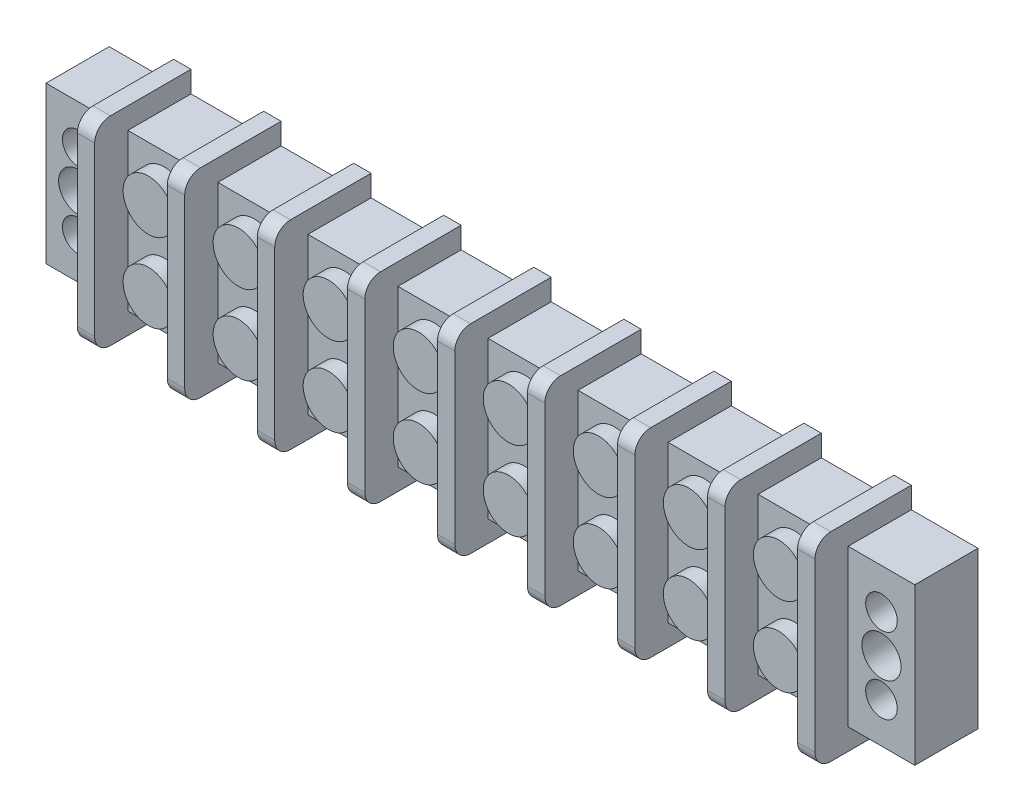
SolidWorks part; units mm, degrees
ref_plane "Front Plane" through (0, 0, 0) normal (0, 0, 1) x (1, 0, 0)
ref_plane "Top Plane" through (0, 0, 0) normal (0, 1, 0) x (1, 0, 0)
ref_plane "Right Plane" through (0, 0, 0) normal (1, 0, 0) x (0, 0, -1)
sketch "Sketch1" plane through (0, 0, 0) normal (0, 0, 1) x (1, 0, 0)
  line L1 (0, 25.146) -> (139.7, 25.146)
  line L2 (0, 25.146) -> (0, 0)
  line L3 (0, 0) -> (139.7, 0)
  line L4 (139.7, 25.146) -> (139.7, 0)
  dimension "D1" = 139.7
  dimension "D2" = 25.146
extrude "Boss-Extrude1" add sketch "Sketch1" along normal blind 10.16
sketch "Sketch3" plane through (0, 0, 0) normal (0, 0, 1) x (1, 0, 0)
  line L0 (0, 12.573) -> (139.7, 12.573) construction
  line L1 (97.2312, 28.575) -> (100.0252, 28.575)
  line L2 (97.2312, 28.575) -> (97.2312, -3.429)
  line L3 (97.2312, -3.429) -> (100.0252, -3.429)
  line L4 (126.1872, 28.575) -> (128.9812, 28.575)
  line L5 (126.1872, 28.575) -> (126.1872, -3.429)
  line L6 (126.1872, -3.429) -> (128.9812, -3.429)
  line L7 (128.9812, 28.575) -> (128.9812, -3.429)
  line L8 (111.7092, 28.575) -> (114.5032, 28.575)
  line L9 (111.7092, 28.575) -> (111.7092, -3.429)
  line L10 (111.7092, -3.429) -> (114.5032, -3.429)
  line L11 (114.5032, 28.575) -> (114.5032, -3.429)
  line L12 (100.0252, 28.575) -> (100.0252, -3.429)
  line L13 (82.7532, 28.575) -> (85.5472, 28.575)
  line L14 (82.7532, 28.575) -> (82.7532, -3.429)
  line L15 (82.7532, -3.429) -> (85.5472, -3.429)
  line L16 (85.5472, 28.575) -> (85.5472, -3.429)
  line L17 (68.2752, 28.575) -> (71.0692, 28.575)
  line L18 (68.2752, 28.575) -> (68.2752, -3.429)
  line L19 (68.2752, -3.429) -> (71.0692, -3.429)
  line L20 (71.0692, 28.575) -> (71.0692, -3.429)
  line L21 (53.7972, 28.575) -> (56.5912, 28.575)
  line L22 (53.7972, 28.575) -> (53.7972, -3.429)
  line L23 (53.7972, -3.429) -> (56.5912, -3.429)
  line L24 (56.5912, 28.575) -> (56.5912, -3.429)
  line L25 (39.3192, 28.575) -> (42.1132, 28.575)
  line L26 (39.3192, 28.575) -> (39.3192, -3.429)
  line L27 (39.3192, -3.429) -> (42.1132, -3.429)
  line L28 (42.1132, 28.575) -> (42.1132, -3.429)
  line L29 (24.8412, 28.575) -> (27.6352, 28.575)
  line L30 (24.8412, 28.575) -> (24.8412, -3.429)
  line L31 (24.8412, -3.429) -> (27.6352, -3.429)
  line L32 (27.6352, 28.575) -> (27.6352, -3.429)
  line L33 (10.3632, 28.575) -> (13.1572, 28.575)
  line L34 (10.3632, 28.575) -> (10.3632, -3.429)
  line L35 (10.3632, -3.429) -> (13.1572, -3.429)
  line L36 (13.1572, 28.575) -> (13.1572, -3.429)
  line L37 (0, 25.146) -> (0, 0) construction
  line L38 (139.7, 0) -> (139.7, 25.146) construction
  point P6 (128.9812, 12.573)
  point P11 (114.5032, 12.573)
  point P16 (100.0252, 12.573)
  point P21 (85.5472, 12.573)
  point P26 (71.0692, 12.573)
  point P31 (56.5912, 12.573)
  point P36 (42.1132, 12.573)
  point P41 (27.6352, 12.573)
  point P46 (13.1572, 12.573)
  point P51 (0, 0)
  dimension "D1" = 2.794
  dimension "D2" = 32.004
  dimension "D3" = 10.7188
  dimension "D4" = 11.684
  dimension "D5" = 11.684
  dimension "D6" = 11.684
  dimension "D7" = 11.684
  dimension "D8" = 11.684
  dimension "D9" = 11.684
  dimension "D10" = 11.684
  dimension "D11" = 11.684
extrude "Boss-Extrude2" add sketch "Sketch3" along normal blind 15.494
fillet "Fillet1" radius 2.54 18 edges at (11.7602, -3.429, 15.494) (26.2382, -3.429, 15.494) (40.7162, -3.429, 15.494) (55.1942, -3.429, 15.494) (69.6722, -3.429, 15.494) (84.1502, -3.429, 15.494) (98.6282, -3.429, 15.494) (113.1062, -3.429, 15.494) (127.5842, -3.429, 15.494) (127.5842, 28.575, 15.494) (113.1062, 28.575, 15.494) (98.6282, 28.575, 15.494) (84.1502, 28.575, 15.494) (69.6722, 28.575, 15.494) (55.1942, 28.575, 15.494) (40.7162, 28.575, 15.494) (26.2382, 28.575, 15.494) (11.7602, 28.575, 15.494)
sketch "Sketch4" plane through (0, 0, 10.16) normal (0, 0, 1) x (1, 0, 0)
  line L0 (18.9992, 18.923) -> (18.9992, 6.223) construction
  line L1 (0, 25.146) -> (0, 0) construction
  line L2 (13.1572, 12.573) -> (24.8412, 12.573) construction
  line L3 (47.9552, 18.923) -> (47.9552, 6.223) construction
  line L5 (33.4772, 18.923) -> (33.4772, 6.223) construction
  line L6 (62.4332, 18.923) -> (62.4332, 6.223) construction
  line L7 (76.9112, 18.923) -> (76.9112, 6.223) construction
  line L8 (91.3892, 18.923) -> (91.3892, 6.223) construction
  line L9 (105.8672, 18.923) -> (105.8672, 6.223) construction
  line L10 (120.3452, 18.923) -> (120.3452, 6.223) construction
  line L11 (27.6352, 12.573) -> (39.3192, 12.573) construction
  line L12 (42.1132, 12.573) -> (53.7972, 12.573) construction
  line L13 (56.5912, 12.573) -> (68.2752, 12.573) construction
  line L14 (71.0692, 12.573) -> (82.7532, 12.573) construction
  line L15 (85.5472, 12.573) -> (97.2312, 12.573) construction
  line L16 (100.0252, 12.573) -> (111.7092, 12.573) construction
  line L17 (114.5032, 12.573) -> (126.1872, 12.573) construction
  line L18 (13.1572, 25.146) -> (13.1572, 0) construction
  line L19 (24.8412, 0) -> (24.8412, 25.146) construction
  line L20 (27.6352, 25.146) -> (27.6352, 0) construction
  line L21 (39.3192, 0) -> (39.3192, 25.146) construction
  line L22 (42.1132, 25.146) -> (42.1132, 0) construction
  line L23 (53.7972, 0) -> (53.7972, 25.146) construction
  line L25 (56.5912, 25.146) -> (56.5912, 0) construction
  line L26 (68.2752, 0) -> (68.2752, 25.146) construction
  line L27 (82.7532, 0) -> (82.7532, 25.146) construction
  line L28 (71.0692, 25.146) -> (71.0692, 0) construction
  line L29 (97.2312, 0) -> (97.2312, 25.146) construction
  line L30 (85.5472, 25.146) -> (85.5472, 0) construction
  line L31 (111.7092, 0) -> (111.7092, 25.146) construction
  line L32 (100.0252, 25.146) -> (100.0252, 0) construction
  line L33 (126.1872, 0) -> (126.1872, 25.146) construction
  line L34 (114.5032, 25.146) -> (114.5032, 0) construction
  circle A0 centre (18.9992, 18.923) radius 4.064
  circle A1 centre (18.9992, 6.223) radius 4.064
  circle A2 centre (47.9552, 18.923) radius 4.064
  circle A3 centre (47.9552, 6.223) radius 4.064
  circle A4 centre (33.4772, 18.923) radius 4.064
  circle A5 centre (33.4772, 6.223) radius 4.064
  circle A6 centre (62.4332, 18.923) radius 4.064
  circle A7 centre (62.4332, 6.223) radius 4.064
  circle A8 centre (76.9112, 18.923) radius 4.064
  circle A9 centre (76.9112, 6.223) radius 4.064
  circle A10 centre (91.3892, 18.923) radius 4.064
  circle A11 centre (91.3892, 6.223) radius 4.064
  circle A12 centre (105.8672, 18.923) radius 4.064
  circle A13 centre (105.8672, 6.223) radius 4.064
  circle A14 centre (120.3452, 18.923) radius 4.064
  circle A15 centre (120.3452, 6.223) radius 4.064
  point P7 (18.9992, 12.573)
  point P22 (47.9552, 12.573)
  point P27 (33.4772, 12.573)
  point P32 (62.4332, 12.573)
  point P37 (76.9112, 12.573)
  point P42 (91.3892, 12.573)
  point P47 (105.8672, 12.573)
  point P52 (120.3452, 12.573)
  dimension "D1" = 8.128
  dimension "D2" = 12.7
extrude "Boss-Extrude3" add sketch "Sketch4" along normal blind 2.54
sketch "Sketch5" plane through (0, 0, 10.16) normal (0, 0, 1) x (1, 0, 0)
  line L0 (134.3406, 25.146) -> (134.3406, 0) construction
  line L1 (5.1816, 25.146) -> (5.1816, 0) construction
  line L2 (139.7, 25.146) -> (128.9812, 25.146) construction
  line L3 (128.9812, 0) -> (139.7, 0) construction
  line L4 (10.3632, 25.146) -> (0, 25.146) construction
  line L5 (0, 0) -> (10.3632, 0) construction
  line L6 (5.1816, 18.669) -> (5.1816, 6.477) construction
  line L7 (0, 25.146) -> (0, 0) construction
  line L8 (134.3406, 18.669) -> (134.3406, 6.477) construction
  circle A0 centre (5.1816, 18.669) radius 2.54
  circle A1 centre (134.3406, 18.669) radius 2.54
  circle A2 centre (134.3406, 12.573) radius 3.1496
  circle A3 centre (5.1816, 6.477) radius 2.54
  circle A4 centre (134.3406, 6.477) radius 2.54
  circle A5 centre (5.1816, 12.573) radius 3.1496
  dimension "D1" = 5.08
  dimension "D2" = 6.2992
  dimension "D3" = 12.192
extrude "Cut-Extrude1" cut sketch "Sketch5" against normal up to surface (10.16 mm away) up to face at (69.6816, 12.573, 0)
